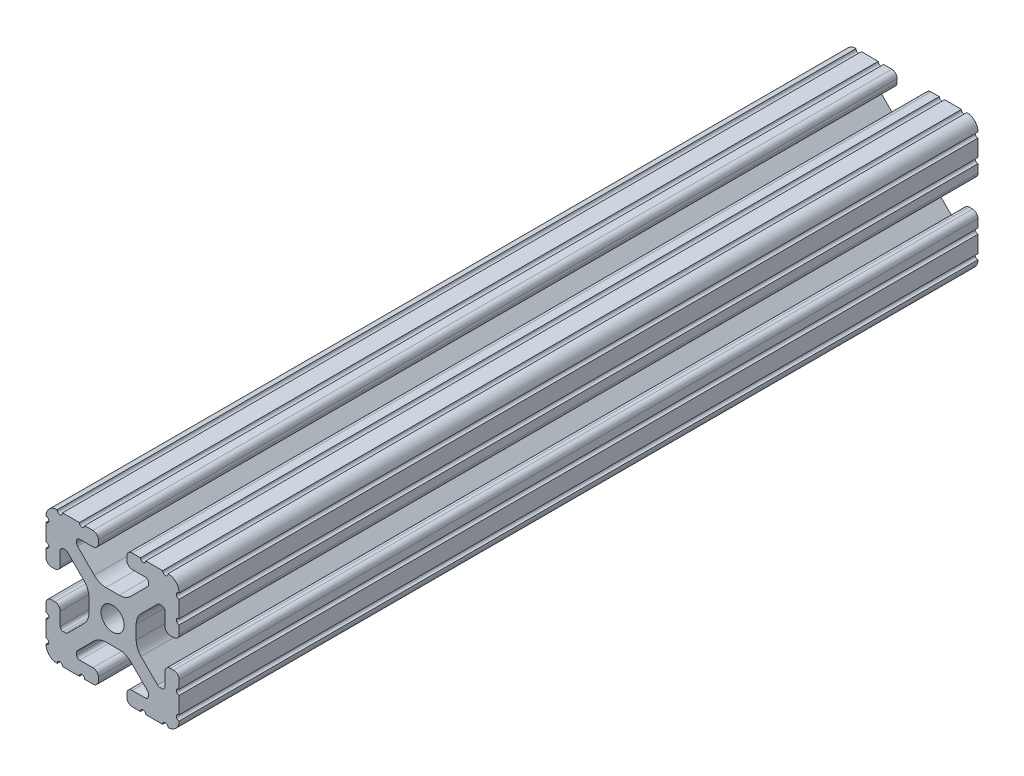
SolidWorks part; units mm, degrees
material "6061 Alloy"
ref_plane "Front Plane" through (0, 0, 0) normal (0, 0, 1) x (1, 0, 0)
ref_plane "Top Plane" through (0, 0, 0) normal (0, 1, 0) x (1, 0, 0)
ref_plane "Right Plane" through (0, 0, 0) normal (1, 0, 0) x (0, 0, -1)
sketch "Sketch1" plane through (0, 0, 0) normal (0, 0, 1) x (1, 0, 0)
  line L0 (0, 25.6181) -> (0, -24.623) construction
  line L1 (-20.8943, 0) -> (20.4607, 0) construction
  line L2 (-10.0229, 12.9148) -> (-5.2522, 8.144)
  line L3 (-10.287, 14.0843) -> (-10.287, 13.5524)
  line L4 (-5.6176, 14.986) -> (-9.3853, 14.986)
  line L5 (-4.064, 17.4964) -> (-4.064, 16.5396)
  line L6 (-7.9742, 19.05) -> (-5.6176, 19.05)
  line L7 (-14.3277, 19.05) -> (-9.4982, 19.05)
  line L8 (-19.05, 9.4961) -> (-19.05, 14.3277)
  line L9 (-19.05, 5.6176) -> (-19.05, 7.9763)
  line L10 (-16.5396, 4.064) -> (-17.4964, 4.064)
  line L11 (-14.986, 9.3853) -> (-14.986, 5.6176)
  line L12 (-13.516, 10.287) -> (-14.0843, 10.287)
  line L13 (-8.1476, 5.2921) -> (-12.8784, 10.0229)
  line L14 (-6.7564, -1.9335) -> (-6.7564, 1.9335)
  line L15 (-12.8784, -10.0229) -> (-8.1476, -5.2921)
  line L16 (-14.0843, -10.287) -> (-13.516, -10.287)
  line L17 (-14.986, -5.6176) -> (-14.986, -9.3853)
  line L18 (-17.4964, -4.064) -> (-16.5396, -4.064)
  line L19 (-19.05, -7.9763) -> (-19.05, -5.6176)
  line L20 (-19.05, -14.3277) -> (-19.05, -9.4961)
  line L21 (-9.4961, -19.05) -> (-14.3277, -19.05)
  line L22 (-5.6176, -19.05) -> (-7.9763, -19.05)
  line L23 (-4.064, -17.4964) -> (-4.064, -16.5396)
  line L24 (10.0229, -12.9148) -> (5.2522, -8.144)
  line L25 (10.287, -14.0843) -> (10.287, -13.5524)
  line L26 (5.6176, -14.986) -> (9.3853, -14.986)
  line L28 (-1.9022, 6.7564) -> (1.9022, 6.7564)
  line L29 (-1.9022, -6.7564) -> (1.9022, -6.7564)
  line L31 (-5.6176, -14.986) -> (-9.3853, -14.986)
  line L32 (-10.287, -14.0843) -> (-10.287, -13.5524)
  line L33 (-10.0229, -12.9148) -> (-5.2522, -8.144)
  line L66 (4.064, -16.5396) -> (4.064, -17.4964)
  line L67 (5.6176, -19.05) -> (7.9763, -19.05)
  line L68 (9.4961, -19.05) -> (14.3277, -19.05)
  line L69 (19.05, -14.3277) -> (19.05, -9.4961)
  line L70 (19.05, -7.9763) -> (19.05, -5.6176)
  line L71 (17.4964, -4.064) -> (16.5396, -4.064)
  line L72 (14.986, -5.6176) -> (14.986, -9.3853)
  line L73 (14.0843, -10.287) -> (13.516, -10.287)
  line L74 (12.8784, -10.0229) -> (8.1476, -5.2921)
  line L75 (6.7564, -1.9335) -> (6.7564, 1.9335)
  line L76 (8.1476, 5.2921) -> (12.8784, 10.0229)
  line L77 (13.516, 10.287) -> (14.0843, 10.287)
  line L78 (14.986, 9.3853) -> (14.986, 5.6176)
  line L79 (16.5396, 4.064) -> (17.4964, 4.064)
  line L80 (19.05, 5.6176) -> (19.05, 7.9763)
  line L81 (19.05, 9.4961) -> (19.05, 14.3277)
  line L82 (14.3277, 19.05) -> (9.4982, 19.05)
  line L83 (7.9742, 19.05) -> (5.6176, 19.05)
  line L84 (4.064, 17.4964) -> (4.064, 16.5396)
  line L85 (5.6176, 14.986) -> (9.3853, 14.986)
  line L86 (10.287, 14.0843) -> (10.287, 13.5524)
  line L87 (10.0229, 12.9148) -> (5.2522, 8.144)
  arc A0 (-10.0229, 12.9148) -> (-10.287, 13.5524) centre (-9.3853, 13.5524) cw
  circle A1 centre (0, 0) radius 3.3274
  arc A2 (-10.287, 14.0843) -> (-9.3853, 14.986) centre (-9.3853, 14.0843) cw
  arc A3 (-4.064, 16.5396) -> (-5.6176, 14.986) centre (-5.6176, 16.5396) cw
  arc A4 (-5.6176, 19.05) -> (-4.064, 17.4964) centre (-5.6176, 17.4964) cw
  arc A5 (-7.9742, 19.05) -> (-9.4982, 19.05) centre (-8.7362, 19.05) cw
  arc A6 (-14.3277, 19.05) -> (-15.8475, 19.05) centre (-15.0876, 18.9933) cw
  arc A7 (-19.05, 15.8475) -> (-15.8475, 19.05) centre (-15.8751, 15.8751) cw
  arc A8 (-19.05, 15.8475) -> (-19.05, 14.3277) centre (-18.9933, 15.0876) cw
  arc A9 (-19.05, 9.4961) -> (-19.05, 7.9763) centre (-18.9933, 8.7362) cw
  arc A10 (-17.4964, 4.064) -> (-19.05, 5.6176) centre (-17.4964, 5.6176) cw
  arc A11 (-14.986, 5.6176) -> (-16.5396, 4.064) centre (-16.5396, 5.6176) cw
  arc A12 (-14.986, 9.3853) -> (-14.0843, 10.287) centre (-14.0843, 9.3853) cw
  arc A13 (-13.516, 10.287) -> (-12.8784, 10.0229) centre (-13.516, 9.3853) cw
  arc A14 (-8.1476, 5.2921) -> (-6.7564, 1.9335) centre (-11.5062, 1.9335) cw
  arc A15 (-6.7564, -1.9335) -> (-8.1476, -5.2921) centre (-11.5062, -1.9335) cw
  arc A16 (-12.8784, -10.0229) -> (-13.516, -10.287) centre (-13.516, -9.3853) cw
  arc A17 (-14.0843, -10.287) -> (-14.986, -9.3853) centre (-14.0843, -9.3853) cw
  arc A18 (-16.5396, -4.064) -> (-14.986, -5.6176) centre (-16.5396, -5.6176) cw
  arc A19 (-19.05, -5.6176) -> (-17.4964, -4.064) centre (-17.4964, -5.6176) cw
  arc A20 (-19.05, -7.9763) -> (-19.05, -9.4961) centre (-18.9933, -8.7362) cw
  arc A21 (-19.05, -14.3277) -> (-19.05, -15.8475) centre (-18.9933, -15.0876) cw
  arc A22 (-15.8475, -19.05) -> (-19.05, -15.8475) centre (-15.8751, -15.8751) cw
  arc A23 (-15.8475, -19.05) -> (-14.3277, -19.05) centre (-15.0876, -18.9933) cw
  arc A24 (-9.4961, -19.05) -> (-7.9763, -19.05) centre (-8.7362, -18.9933) cw
  arc A25 (-4.064, -17.4964) -> (-5.6176, -19.05) centre (-5.6176, -17.4964) cw
  arc A26 (-5.2522, -8.144) -> (-1.9022, -6.7564) centre (-1.9022, -11.494) cw
  arc A27 (1.9022, -6.7564) -> (5.2522, -8.144) centre (1.9022, -11.494) cw
  arc A28 (10.0229, -12.9148) -> (10.287, -13.5524) centre (9.3853, -13.5524) cw
  arc A29 (10.287, -14.0843) -> (9.3853, -14.986) centre (9.3853, -14.0843) cw
  arc A30 (4.064, -16.5396) -> (5.6176, -14.986) centre (5.6176, -16.5396) cw
  arc A31 (-4.064, -16.5396) -> (-5.6176, -14.986) centre (-5.6176, -16.5396) ccw
  arc A32 (-10.287, -14.0843) -> (-9.3853, -14.986) centre (-9.3853, -14.0843) ccw
  arc A33 (-10.0229, -12.9148) -> (-10.287, -13.5524) centre (-9.3853, -13.5524) ccw
  arc A79 (4.064, -17.4964) -> (5.6176, -19.05) centre (5.6176, -17.4964) ccw
  arc A80 (9.4961, -19.05) -> (7.9763, -19.05) centre (8.7362, -18.9933) ccw
  arc A81 (15.8475, -19.05) -> (14.3277, -19.05) centre (15.0876, -18.9933) ccw
  arc A82 (15.8475, -19.05) -> (19.05, -15.8475) centre (15.8751, -15.8751) ccw
  arc A83 (19.05, -14.3277) -> (19.05, -15.8475) centre (18.9933, -15.0876) ccw
  arc A84 (19.05, -7.9763) -> (19.05, -9.4961) centre (18.9933, -8.7362) ccw
  arc A85 (19.05, -5.6176) -> (17.4964, -4.064) centre (17.4964, -5.6176) ccw
  arc A86 (16.5396, -4.064) -> (14.986, -5.6176) centre (16.5396, -5.6176) ccw
  arc A87 (14.0843, -10.287) -> (14.986, -9.3853) centre (14.0843, -9.3853) ccw
  arc A88 (12.8784, -10.0229) -> (13.516, -10.287) centre (13.516, -9.3853) ccw
  arc A89 (6.7564, -1.9335) -> (8.1476, -5.2921) centre (11.5062, -1.9335) ccw
  arc A90 (8.1476, 5.2921) -> (6.7564, 1.9335) centre (11.5062, 1.9335) ccw
  arc A91 (13.516, 10.287) -> (12.8784, 10.0229) centre (13.516, 9.3853) ccw
  arc A92 (14.986, 9.3853) -> (14.0843, 10.287) centre (14.0843, 9.3853) ccw
  arc A93 (14.986, 5.6176) -> (16.5396, 4.064) centre (16.5396, 5.6176) ccw
  arc A94 (17.4964, 4.064) -> (19.05, 5.6176) centre (17.4964, 5.6176) ccw
  arc A95 (19.05, 9.4961) -> (19.05, 7.9763) centre (18.9933, 8.7362) ccw
  arc A96 (19.05, 15.8475) -> (19.05, 14.3277) centre (18.9933, 15.0876) ccw
  arc A97 (19.05, 15.8475) -> (15.8475, 19.05) centre (15.8751, 15.8751) ccw
  arc A98 (14.3277, 19.05) -> (15.8475, 19.05) centre (15.0876, 18.9933) ccw
  arc A99 (7.9742, 19.05) -> (9.4982, 19.05) centre (8.7362, 19.05) ccw
  arc A100 (5.6176, 19.05) -> (4.064, 17.4964) centre (5.6176, 17.4964) ccw
  arc A101 (4.064, 16.5396) -> (5.6176, 14.986) centre (5.6176, 16.5396) ccw
  arc A102 (10.287, 14.0843) -> (9.3853, 14.986) centre (9.3853, 14.0843) ccw
  arc A103 (10.0229, 12.9148) -> (10.287, 13.5524) centre (9.3853, 13.5524) ccw
  arc A104 (1.9022, 6.7564) -> (5.2522, 8.144) centre (1.9022, 11.494) ccw
  arc A105 (-5.2522, 8.144) -> (-1.9022, 6.7564) centre (-1.9022, 11.494) ccw
  dimension "D1" = 6.6548
  dimension "D2" = 19.05
  dimension "D3" = 38.1
  dimension "D4" = 20.574
  dimension "D5" = 13.5128
  dimension "D6" = 4.064
  dimension "D7" = 8.128
  dimension "D8" = 4.064
  dimension "D9" = 12.2936
extrude "Extrude1" add sketch "Sketch1" against normal blind 228.6
